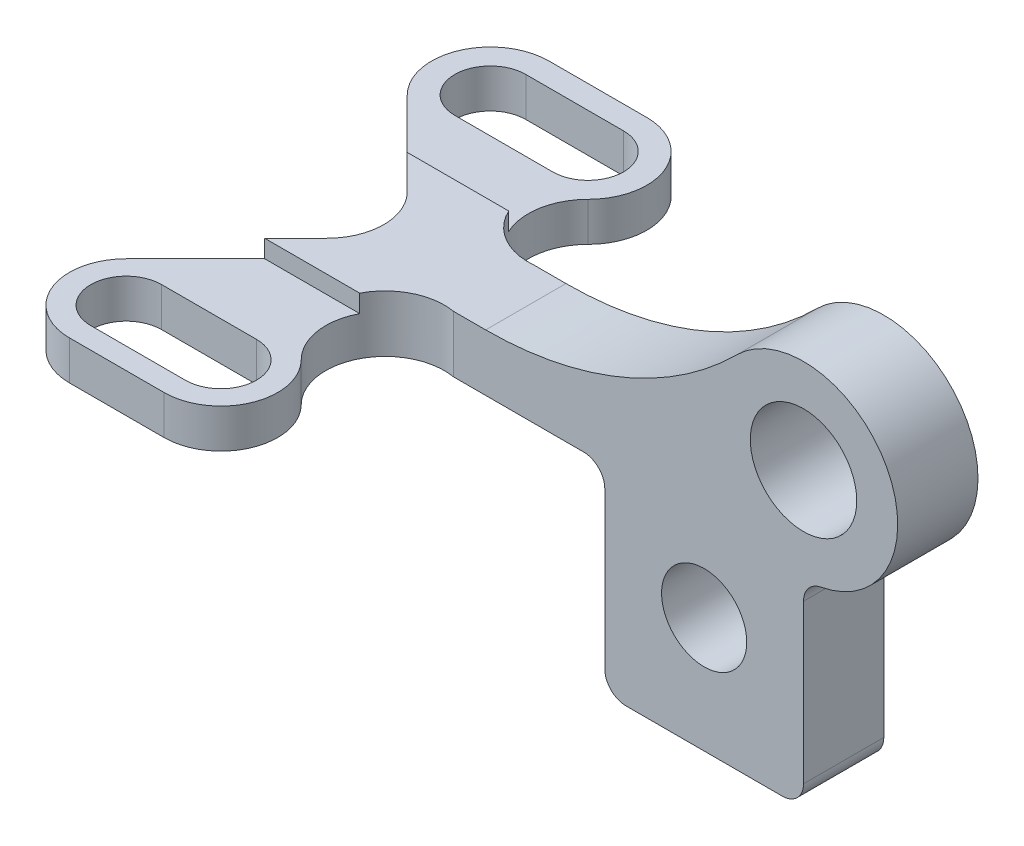
SolidWorks part; units mm, degrees
ref_plane "Front Plane" through (0, 0, 0) normal (0, 0, 1) x (1, 0, 0)
ref_plane "Top Plane" through (0, 0, 0) normal (0, 1, 0) x (1, 0, 0)
ref_plane "Right Plane" through (0, 0, 0) normal (1, 0, 0) x (0, 0, -1)
sketch "Sketch1" plane through (0, 0, 0) normal (0, 1, 0) x (1, 0, 0)
  line L0 (-46.0843, 26.1008) -> (-18.5197, 26.1008)
  line L1 (-46.0843, 6.1008) -> (-18.5197, 6.1008)
  line L2 (-46.0843, 32.6494) -> (-18.5197, 32.6494)
  line L3 (-46.0843, 16.1008) -> (-46.0843, 2.2038) construction
  line L4 (-46.0843, 16.1008) -> (-57.398, 4.7871) construction
  line L5 (-57.786, 4.3992) -> (-29.1138, -24.273)
  line L6 (-29.1138, -46.9005) -> (-57.398, -75.1847)
  line L7 (-46.0843, -102.4984) -> (-19.3974, -102.4984)
  line L8 (-46.0843, -76.4984) -> (-19.3974, -76.4984)
  line L9 (-46.0843, -96.4984) -> (-19.3974, -96.4984)
  line L10 (-19.3974, -86.4984) -> (12.9001, -86.4984) construction
  line L11 (-19.3974, -86.4984) -> (6.5801, -60.5209) construction
  line L12 (-18.5197, 16.1008) -> (12.9001, 16.1008) construction
  line L13 (-18.5197, 16.1008) -> (6.5801, -8.9989) construction
  line L14 (6.5801, -24.273) -> (89.5801, -24.273)
  line L15 (6.5801, -46.9005) -> (89.5801, -46.9005)
  line L16 (89.5801, -24.273) -> (89.5801, -46.9005)
  arc A0 (-46.0843, 26.1008) -> (-46.0843, 6.1008) centre (-46.0843, 16.1008) ccw
  arc A1 (-18.5197, 26.1008) -> (-18.5197, 6.1008) centre (-18.5197, 16.1008) cw
  arc A2 (-18.5197, 32.6494) -> (-6.818, 4.3992) centre (-18.5197, 16.1008) cw
  arc A3 (-46.0843, 32.6494) -> (-57.786, 4.3992) centre (-46.0843, 16.1008) ccw
  arc A4 (-29.1138, -24.273) -> (-29.1138, -46.9005) centre (-40.4275, -35.5868) cw
  arc A5 (-57.398, -75.1847) -> (-46.0843, -102.4984) centre (-46.0843, -86.4984) ccw
  arc A6 (-46.0843, -96.4984) -> (-46.0843, -76.4984) centre (-46.0843, -86.4984) cw
  arc A7 (-19.3974, -76.4984) -> (-19.3974, -96.4984) centre (-19.3974, -86.4984) cw
  arc A8 (-19.3974, -102.4984) -> (-8.0837, -75.1847) centre (-19.3974, -86.4984) ccw
  arc A9 (-6.818, 4.3992) -> (6.5801, -24.273) centre (5.0859, -7.5048) ccw
  arc A10 (-8.0837, -75.1847) -> (6.5801, -46.9005) centre (3.7332, -63.3678) cw
  dimension "D1" = 16
  dimension "D2" = 45
extrude "Boss-Extrude1" add sketch "Sketch1" along normal blind 16
sketch "Sketch2" plane through (0, 0, 46.9005) normal (0, 0, 1) x (1, 0, 0)
  line L0 (-62.0843, 16) -> (-62.0843, 0) construction
  line L1 (6.5801, 0) -> (89.5801, 0) construction
  line L2 (105.1857, 0) -> (105.1857, -56)
  line L3 (105.1857, -56) -> (49.1857, -56)
  line L4 (49.1857, -56) -> (49.1857, 0)
  line L5 (105.1857, 26.55) -> (71.9299, 59.8057) construction
  line L6 (6.5801, 16) -> (89.5801, 16) construction
  circle A0 centre (77.1857, -23.45) radius 12
  circle A1 centre (105.1857, 26.55) radius 15
  arc A2 (105.1857, 0) -> (86.412, 45.3237) centre (105.1857, 26.55) ccw
  arc A3 (86.412, 45.3237) -> (15.6183, 16) centre (15.6183, 116.1173) cw
  dimension "D1" = 139.27
  dimension "D2" = 23.45
  dimension "D3" = 28
  dimension "D4" = 50
extrude "Boss-Extrude2" add sketch "Sketch2" against normal up to vertex
fillet "Fillet1" radius 6 4 edges at (105.1857, 0, 35.5868) (49.1857, 0, 35.5868) (105.1857, -56, 35.5868) (49.1857, -56, 35.5868)
sketch "Sketch6" plane through (0, 0, 102.4984) normal (0, 0, 1) x (1, 0, 0)
  line L5 (-3.3974, 0) -> (-3.3974, 16) construction
  line L6 (-62.6329, 16) -> (-3.3974, 16)
  line L7 (-62.6329, 16) -> (-62.6329, 11)
  line L8 (-62.6329, 11) -> (-3.3974, 11)
  line L9 (-3.3974, 16) -> (-3.3974, 11)
sketch "Sketch8" plane through (0, 16, 0) normal (0, 1, 0) x (1, 0, 0)
  line L0 (15.6183, -35.5868) -> (-24.4275, -35.5868) construction
  line L1 (15.6183, -24.273) -> (15.6183, -46.9005) construction
  line L2 (-10.1658, -14.6317) -> (-38.7551, -14.6317)
  line L3 (-57.786, 4.3992) -> (-29.1138, -24.273) construction
  line L4 (-11.1031, -55.676) -> (-37.8894, -55.676)
  line L5 (-29.1138, -46.9005) -> (-57.398, -75.1847) construction
  arc A0 (-29.1138, -46.9005) -> (-29.1138, -24.273) centre (-40.4275, -35.5868) ccw construction
  arc A1 (-6.818, 4.3992) -> (6.5801, -24.273) centre (5.0859, -7.5048) ccw construction
  arc A2 (6.5801, -46.9005) -> (-8.0837, -75.1847) centre (3.7332, -63.3678) ccw construction
  point P21 (0, 0)
  point P22 (0, 0)
extrude "Cut-Extrude3" cut sketch "Sketch6" against normal up to vertex (46.8224 mm away) contours L7 L8 L9 L6 up to point (-37.8894, 16, 55.676)
sketch "Sketch9" plane through (0, 0, -32.6494) normal (0, 0, -1) x (-1, 0, 0)
  line L0 (62.6329, 0) -> (62.6329, 16) construction
  line L1 (1.971, 16) -> (62.6329, 16)
  line L2 (1.971, 16) -> (1.971, 11)
  line L3 (1.971, 11) -> (62.6329, 11)
  line L4 (62.6329, 16) -> (62.6329, 11)
extrude "Cut-Extrude4" cut sketch "Sketch9" against normal up to vertex (47.2811 mm away) up to point (-38.7551, 16, 14.6317)
